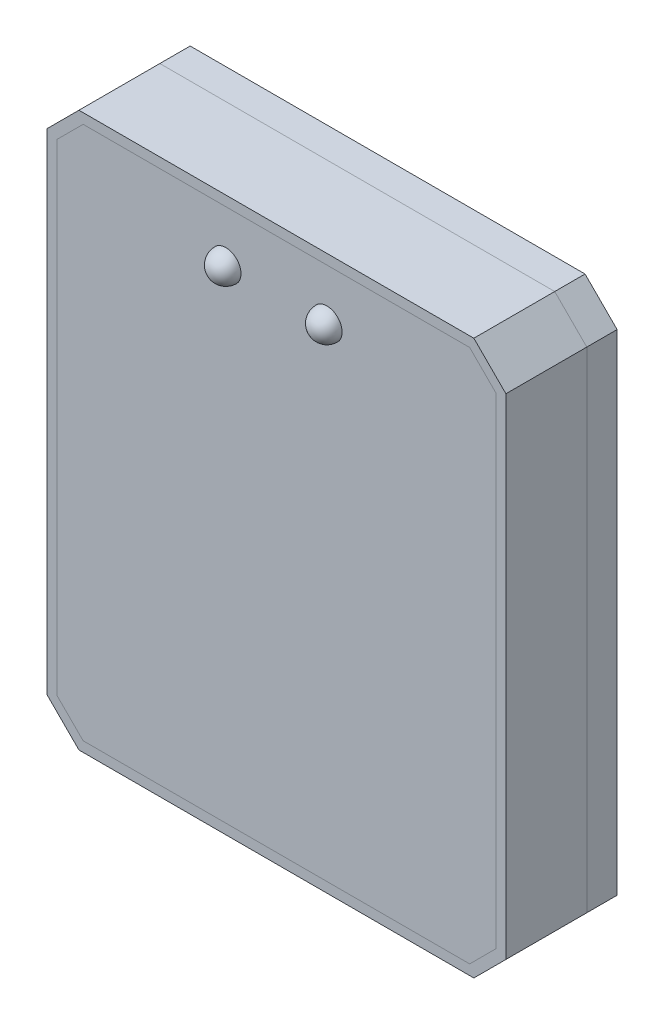
SolidWorks part; units mm, degrees
other "NFC"
other "LED red"
other "LED green"
other "Case" parameters "D3"=10, "D4"=10, "D5"=10, "D6"=10, "D7"=2, "D8"=2, "D9"=2, "D10"=2, "D11"=10, "D12"=2, "D13"=2, "D14"=2, "D15"=2, "D16"=2, "D1"=2, "D17"=2, "D18"=2, "D19"=2, "D20"=2
ref_plane "Front Plane" through (0, 0, 0) normal (0, 0, 1) x (1, 0, 0)
ref_plane "Top Plane" through (0, 0, 0) normal (0, 1, 0) x (1, 0, 0)
ref_plane "Right Plane" through (0, 0, 0) normal (1, 0, 0) x (0, 0, -1)
sketch "Sketch1" plane through (0, 0, 0) normal (0, 0, 1) x (1, 0, 0)
  line L9 (-18.5, 21.6) -> (-20.5, 19.6)
  line L10 (18.5, -21.6) -> (-18.5, -21.6)
  line L14 (20.5, -19.6) -> (20.5, 19.6)
  line L15 (18.5, 21.6) -> (-18.5, 21.6)
  line L16 (-20.5, -19.6) -> (-20.5, 19.6)
  line L17 (0, 21.6) -> (0, -21.6) construction
  line L18 (20.5, 0) -> (-20.5, 0) construction
  line L19 (20.5, -19.6) -> (18.5, -21.6)
  line L20 (20.5, 19.6) -> (18.5, 21.6)
  line L21 (-18.5, -21.6) -> (-20.5, -19.6)
  point P0 (0, 0)
  point P1 (-20.5, 21.6)
  point P2 (20.5, -21.6)
  point P3 (20.5, 21.6)
  point P129 (-20.5, -21.6)
  dimension "D1" = 41
  dimension "D2" = 43.2
extrude "Boss-Extrude1" add sketch "Sketch1" against normal blind 1.7
sketch "Sketch2" plane through (0, 0, 0) normal (0, 0, 1) x (1, 0, 0)
  line L0 (0, 0) -> (0, 50000) construction
  circle A0 centre (-5, 25) radius 1.95
  dimension "D1" = 3.9
  dimension "D2" = 10
  dimension "D3" = 25
extrude "Boss-Extrude2" add sketch "Sketch2" against normal blind 0.8 separate body
sketch "Sketch4" plane through (0, 0, 0) normal (0, 0, 1) x (1, 0, 0)
  circle A0 centre (-5, 25) radius 1.5
  dimension "D1" = 3
extrude "Boss-Extrude3" add sketch "Sketch4" along normal blind 4.5
fillet "Fillet1" radius 1.5 1 edges at (-3.5, 25, 4.5)
mirror "LED green" about plane through (0, 0, 0) normal (1, 0, 0) of bodies 103
sketch "Sketch6" plane through (0, 0, 0) normal (0, 0, 1) x (1, 0, 0)
  line L1 (-18.7, -21.8) -> (18.7, -21.8)
  line L2 (-20.7, -19.8) -> (-20.7, 27)
  line L3 (-18.7, 29) -> (18.7, 29)
  line L4 (20.7, -19.8) -> (20.7, 27)
  line L6 (-18.5, -21.6) -> (18.5, -21.6) construction
  line L7 (-20.5, 19.6) -> (-20.5, -19.6) construction
  line L8 (-20.7, 27) -> (-18.7, 29)
  line L9 (18.7, 29) -> (20.7, 27)
  line L10 (18.7, -21.8) -> (20.7, -19.8)
  line L11 (-18.7, -21.8) -> (-20.7, -19.8)
  line L12 (-19.5284, 31) -> (19.5284, 31)
  line L13 (19.5284, 31) -> (22.7, 27.8284)
  line L14 (22.7, -20.6284) -> (22.7, 27.8284)
  line L15 (19.5284, -23.8) -> (22.7, -20.6284)
  line L16 (-19.5284, -23.8) -> (19.5284, -23.8)
  line L17 (-19.5284, -23.8) -> (-22.7, -20.6284)
  line L18 (-22.7, -20.6284) -> (-22.7, 27.8284)
  line L19 (-22.7, 27.8284) -> (-19.5284, 31)
  circle A0 centre (-5, 25) radius 4 construction
  point P1 (20.7, 29)
  point P2 (-20.7, 29)
  point P4 (-20.7, -21.8)
  point P6 (20.7, -21.8)
  point P22 (0, -21.8)
  dimension "D4" = 8
  dimension "D5" = 2
  dimension "D2" = 0.2
  dimension "D3" = 0.2
extrude "Boss-Extrude4" add sketch "Sketch6" against normal blind 5 separate body
sketch "Sketch7" plane through (0, 0, 0) normal (0, 0, 1) x (1, 0, 0)
  line L8 (22.7, 27.8284) -> (19.5284, 31)
  line L9 (19.5284, 31) -> (-19.5284, 31)
  line L10 (-19.5284, 31) -> (-22.7, 27.8284)
  line L11 (-22.7, 27.8284) -> (-22.7, -20.6284)
  line L12 (-22.7, -20.6284) -> (-19.5284, -23.8)
  line L13 (-19.5284, -23.8) -> (19.5284, -23.8)
  line L14 (19.5284, -23.8) -> (22.7, -20.6284)
  line L15 (22.7, -20.6284) -> (22.7, 27.8284)
  line L16 (21.7, 27.4142) -> (19.1142, 30)
  line L17 (21.7, -20.2142) -> (21.7, 27.4142)
  line L18 (19.1142, -22.8) -> (21.7, -20.2142)
  line L19 (-19.1142, -22.8) -> (19.1142, -22.8)
  line L20 (-21.7, -20.2142) -> (-19.1142, -22.8)
  line L21 (-21.7, 27.4142) -> (-21.7, -20.2142)
  line L22 (-19.1142, 30) -> (-21.7, 27.4142)
  line L23 (19.1142, 30) -> (-19.1142, 30)
  line L24 (21.7, 27.4142) -> (19.1142, 30)
  line L25 (21.7, -20.2142) -> (21.7, 27.4142)
  line L26 (19.1142, -22.8) -> (21.7, -20.2142)
  line L27 (-19.1142, -22.8) -> (19.1142, -22.8)
  line L28 (-21.7, -20.2142) -> (-19.1142, -22.8)
  line L29 (-21.7, 27.4142) -> (-21.7, -20.2142)
  line L30 (-19.1142, 30) -> (-21.7, 27.4142)
  line L31 (19.1142, 30) -> (-19.1142, 30)
  dimension "D1" = 1
  dimension "D2" = 1
extrude "Boss-Extrude5" add sketch "Sketch7" along normal blind 3
sketch "Sketch8" plane through (0, 0, -5) normal (0, 0, -1) x (-1, 0, 0)
  line L0 (-18.7, 29) -> (-20.7, 27)
  line L1 (-20.7, 27) -> (-20.7, 23)
  line L2 (-20.7, -19.8) -> (-20.7, 27) construction
  line L3 (-17.7, 23) -> (-20.7, 23)
  line L4 (-18.7, 29) -> (-14.7, 29)
  line L5 (18.7, 29) -> (-18.7, 29) construction
  line L6 (-14.7, 29) -> (-14.7, 26)
  circle A0 centre (-17.7, 26) radius 3 construction
  circle A1 centre (-17.7, 26) radius 1.2
  arc A3 (-14.7, 26) -> (-17.7, 23) centre (-17.7, 26) cw
  line M11 (-20.7, -19.8) -> (-20.7, 27)
  line M12 (-20.7, 27) -> (-18.7, 29)
  line M13 (-18.7, 29) -> (18.7, 29)
  dimension "D1" = 6
  dimension "D2" = 2.4
extrude "Boss-Extrude6" add sketch "Sketch8" against normal blind 3 contours A3 L6 L3 A1 M13 M12 M11
mirror "Mirror1" about plane through (0, 0, 0) normal (1, 0, 0) of "Boss-Extrude6"
ref_plane "Plane1" through (0, 3.6, 0) normal (0, 1, 0) x (1, 0, 0)
mirror "Mirror2" about plane through (0, 3.6, 0) normal (0, 1, 0) of "Mirror1", "Boss-Extrude6"
sketch "Sketch9" plane through (0, 0, 0) normal (0, 0, 1) x (1, 0, 0)
  line L0 (-21.7, 27.4142) -> (-19.1142, 30)
  line L1 (-19.1142, 30) -> (19.1142, 30)
  line L2 (19.1142, 30) -> (21.7, 27.4142)
  line L3 (21.7, 27.4142) -> (21.7, -20.2142)
  line L4 (21.7, -20.2142) -> (19.1142, -22.8)
  line L5 (19.1142, -22.8) -> (-19.1142, -22.8)
  line L6 (-19.1142, -22.8) -> (-21.7, -20.2142)
  line L7 (-21.7, -20.2142) -> (-21.7, 27.4142)
  circle A0 centre (-5, 25) radius 1.5
  circle A1 centre (5, 25) radius 1.5
  circle A2 centre (-5, 25) radius 1.5 construction
  circle A3 centre (5, 25) radius 1.5 construction
  dimension "D1" = 3
  dimension "D2" = 3
extrude "Front" add sketch "Sketch9" along normal up to surface (3 mm away) separate body up to face at (0, 3.6, 3)
sketch "Sketch10" plane through (0, 0, -5) normal (0, 0, -1) x (-1, 0, 0)
  line L0 (-22.7, 27.8284) -> (-19.5284, 31)
  line L1 (19.5284, 31) -> (-19.5284, 31) construction
  line L2 (-19.5284, 31) -> (-22.7, 27.8284) construction
  line L3 (-19.5284, 31) -> (19.5284, 31)
  line L4 (19.5284, 31) -> (22.7, 27.8284)
  line L5 (22.7, 27.8284) -> (22.7, -20.6284)
  line L6 (22.7, -20.6284) -> (19.5284, -23.8)
  line L7 (19.5284, -23.8) -> (-19.5284, -23.8)
  line L8 (-19.5284, -23.8) -> (-22.7, -20.6284)
  line L9 (-22.7, -20.6284) -> (-22.7, 27.8284)
  circle A0 centre (-17.7, 26) radius 1.6
  circle A1 centre (17.7, 26) radius 1.6
  circle A2 centre (17.7, -18.8) radius 1.6
  circle A3 centre (-17.7, -18.8) radius 1.6
  dimension "D1" = 3.2
extrude "Back" add sketch "Sketch10" along normal blind 3 separate body
